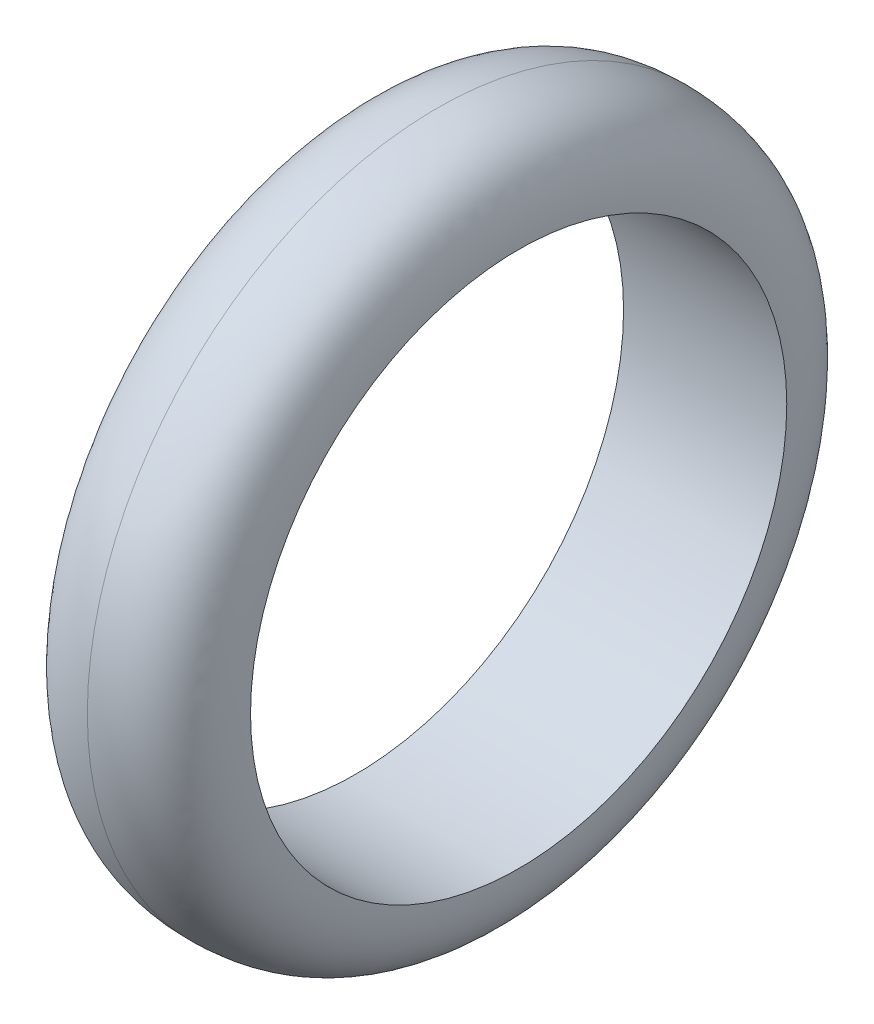
SolidWorks part; units mm, degrees
ref_plane "Front Plane" through (0, 0, 0) normal (0, 0, 1) x (1, 0, 0)
ref_plane "Top Plane" through (0, 0, 0) normal (0, 1, 0) x (1, 0, 0)
ref_plane "Right Plane" through (0, 0, 0) normal (1, 0, 0) x (0, 0, -1)
sketch "Sketch1" plane through (0, 0, 0) normal (0, 0, 1) x (1, 0, 0)
  line L0 (-8.89, 29.21) -> (8.89, 29.21)
  line L1 (0, 0) -> (0, 4.1835) construction
  line L2 (8.89, 29.21) -> (8.89, 38.1) construction
  line L3 (8.89, 38.1) -> (0, 38.1) construction
  line L4 (-8.89, 29.21) -> (-8.89, 38.1) construction
  line L5 (-8.89, 38.1) -> (0, 38.1) construction
  line L6 (0, 0) -> (39.6195, 0) construction
  spline S0 degree 2 poles (8.89, 29.21) (8.89, 38.1) (0, 38.1) knots 0 0 0 1 1 1
  spline S1 degree 2 poles (-8.89, 29.21) (-8.89, 38.1) (0, 38.1) knots 0 0 0 1 1 1
  dimension "D1" = 17.78
  dimension "D2" = 29.21
  dimension "D3" = 8.89
revolve "Revolve1" add sketch "Sketch1" angle 360 about L6
